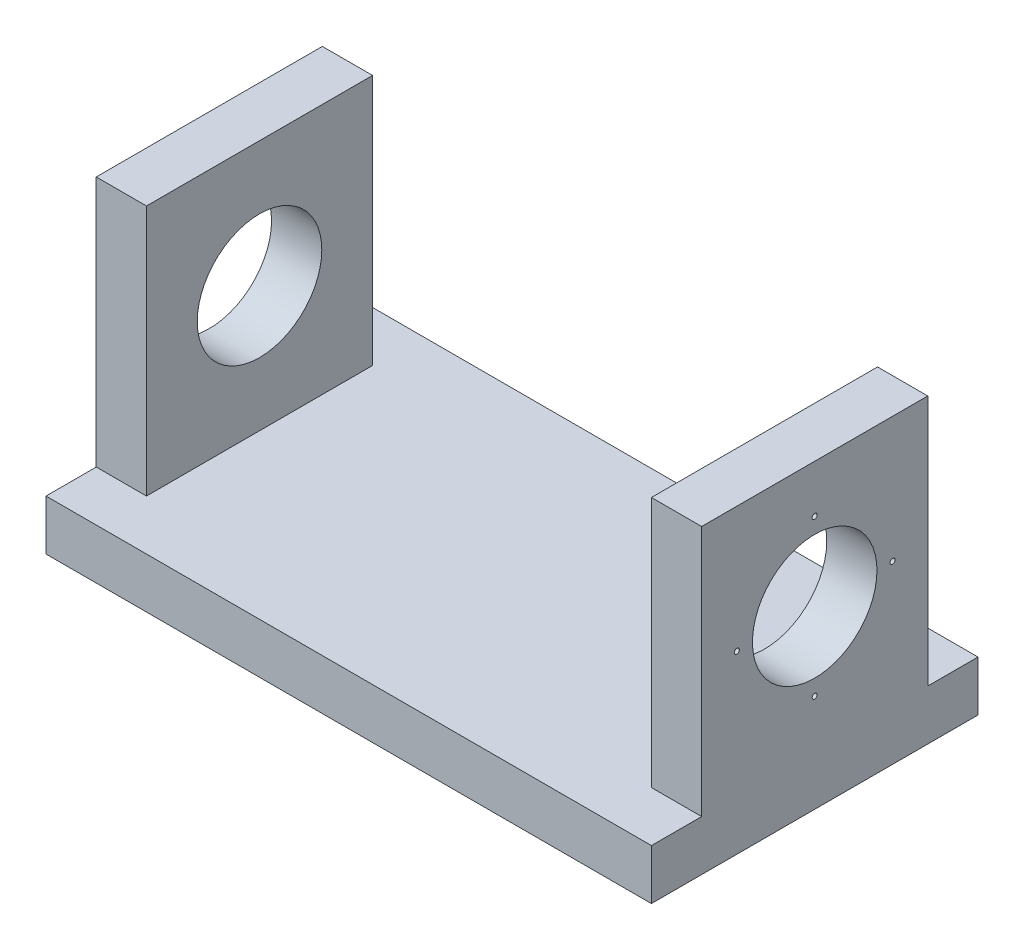
SolidWorks part; units mm, degrees
ref_plane "Front Plane" through (0, 0, 0) normal (0, 0, 1) x (1, 0, 0)
ref_plane "Top Plane" through (0, 0, 0) normal (0, 1, 0) x (1, 0, 0)
ref_plane "Right Plane" through (0, 0, 0) normal (1, 0, 0) x (0, 0, -1)
sketch "Sketch2" plane through (0, 0, 0) normal (0, 1, 0) x (1, 0, 0)
  line L0 (100.5, 45) -> (120.5, 45)
  line L1 (100.5, 45) -> (100.5, -45)
  line L2 (100.5, -45) -> (120.5, -45)
  line L3 (-100.2, -480) -> (100.2, -480) construction
  line L4 (100.2, -480) -> (100.2, 480) construction
  line L5 (100.2, 480) -> (-100.2, 480) construction
  line L6 (-100.2, 480) -> (-100.2, -480) construction
  line L7 (120.5, 45) -> (120.5, -45)
  line L8 (-100.5, 45) -> (-120.5, 45)
  line L9 (-100.5, 45) -> (-100.5, -45)
  line L10 (-100.5, -45) -> (-120.5, -45)
  line L11 (-120.5, 45) -> (-120.5, -45)
  line L12 (-120.5, -12.5) -> (120.5, -12.5) construction
  line L13 (-120.5, -12.5) -> (-120.5, 12.5) construction
  line L14 (-120.5, 12.5) -> (120.5, 12.5) construction
  line L15 (120.5, -12.5) -> (120.5, 12.5) construction
  line L16 (-120.5, -12.5) -> (120.5, 12.5) construction
  line L17 (-120.5, 12.5) -> (120.5, -12.5) construction
  circle A0 centre (0, 0) radius 128.6283
  circle A1 centre (0, 0) radius 55
  circle A2 centre (0, 0) radius 48.4
  point P13 (0, 0)
sketch "Sketch3" plane through (0, 0, 0) normal (0, 1, 0) x (1, 0, 0)
  line L0 (100.5, 45) -> (120.5, 45) construction
  line L1 (120.5, 45) -> (120.5, -45) construction
  line L2 (100.5, -45) -> (120.5, -45) construction
  line L3 (100.5, 45) -> (100.5, -45) construction
  line L4 (-100.5, 45) -> (-120.5, 45) construction
  line L5 (-120.5, 45) -> (-120.5, -45) construction
  line L6 (-100.5, -45) -> (-120.5, -45) construction
  line L7 (-100.5, 45) -> (-100.5, -45) construction
  line L8 (100.5, 45) -> (120.5, 45)
  line L9 (120.5, 45) -> (120.5, -45)
  line L10 (100.5, -45) -> (120.5, -45)
  line L11 (100.5, 45) -> (100.5, -45)
  line L12 (-100.5, 45) -> (-120.5, 45)
  line L13 (-120.5, 45) -> (-120.5, -45)
  line L14 (-100.5, -45) -> (-120.5, -45)
  line L15 (-100.5, 45) -> (-100.5, -45)
  circle A0 centre (0, 0) radius 55 construction
  circle A1 centre (0, 0) radius 128.6283 construction
  circle A2 centre (0, 0) radius 55
  circle A3 centre (0, 0) radius 128.6283
sketch "Sketch5" plane through (0, 0, 0) normal (0, 1, 0) x (1, 0, 0)
  line L0 (-120.5, 45) -> (-120.5, -45) construction
  line L1 (-120.5, -65) -> (120.5, -65)
  line L2 (-120.5, -65) -> (-120.5, 65)
  line L3 (-120.5, 65) -> (120.5, 65)
  line L4 (120.5, -65) -> (120.5, 65)
  line L5 (-120.5, -65) -> (120.5, 65) construction
  line L6 (-120.5, 65) -> (120.5, -65) construction
  point P0 (0, 0)
  dimension "D1" = 130
extrude "Boss-Extrude2" add sketch "Sketch5" against normal blind 20
sketch "Sketch6" plane through (0, 0, 0) normal (0, 1, 0) x (1, 0, 0)
  line L0 (100.5, 45) -> (120.5, 45) construction
  line L1 (120.5, 45) -> (120.5, -45) construction
  line L2 (100.5, -45) -> (120.5, -45) construction
  line L3 (100.5, 45) -> (100.5, -45) construction
  line L4 (-100.5, 45) -> (-120.5, 45) construction
  line L5 (-120.5, 45) -> (-120.5, -45) construction
  line L6 (-100.5, -45) -> (-120.5, -45) construction
  line L7 (-100.5, 45) -> (-100.5, -45) construction
  line L8 (100.5, 45) -> (120.5, 45)
  line L9 (120.5, 45) -> (120.5, -45)
  line L10 (100.5, -45) -> (120.5, -45)
  line L11 (100.5, 45) -> (100.5, -45)
  line L12 (-100.5, 45) -> (-120.5, 45)
  line L13 (-120.5, 45) -> (-120.5, -45)
  line L14 (-100.5, -45) -> (-120.5, -45)
  line L15 (-100.5, 45) -> (-100.5, -45)
extrude "Boss-Extrude3" add sketch "Sketch6" along normal blind 100
sketch "Sketch7" plane through (-100.5, 0, 0) normal (1, 0, 0) x (0, 0, -1)
  line L0 (-60, 120) -> (60, 120)
  line L1 (-60, 120) -> (-60, 0)
  line L2 (-60, 0) -> (60, 0)
  line L3 (60, 120) -> (60, 0)
  line L4 (-45, 0) -> (45, 0)
  line L5 (45, 0) -> (45, 100)
  line L6 (45, 100) -> (-45, 100)
  line L7 (-45, 100) -> (-45, 0)
  line L8 (-45, 0) -> (45, 0)
  line L9 (45, 0) -> (45, 100)
  line L10 (45, 100) -> (-45, 100)
  line L11 (-45, 100) -> (-45, 0)
  line L12 (-45, 50) -> (45, 50) construction
  line L14 (-13, 63) -> (13, 63)
  line L15 (-13, 63) -> (-13, 37)
  line L16 (-13, 37) -> (13, 37)
  line L17 (13, 63) -> (13, 37)
  line L18 (0, 63) -> (0, 37) construction
  line L19 (13, 50) -> (-13, 50) construction
  circle A0 centre (0, 50) radius 18.3848 construction
  circle A1 centre (0, 50) radius 21.3848
  circle A2 centre (0, 50) radius 21.5848
  circle A3 centre (0, 50) radius 24.5848
  dimension "D1" = 0
sketch "Sketch8" plane through (120.5, 0, 0) normal (1, 0, 0) x (0, 0, -1)
  circle A2 centre (0, 50) radius 24.5848 construction
  circle A3 centre (0, 50) radius 24.5848 construction
  circle A4 centre (0, 50) radius 24.7848
  dimension "D1" = 0.2
extrude "Cut-Extrude1" cut sketch "Sketch8" against normal through all both and the other way through all
sketch "Sketch9" plane through (0, -20, 0) normal (0, -1, 0) x (1, 0, 0)
  circle A0 centre (0, 0) radius 15.5
  dimension "D1" = 31
extrude "Cut-Extrude2" cut sketch "Sketch9" against normal blind 10
sketch "Sketch10" plane through (120.5, 0, 0) normal (1, 0, 0) x (0, 0, -1)
  circle A0 centre (0, 81) radius 1
  circle A1 centre (-31, 50) radius 1
  circle A2 centre (31, 50) radius 1
  circle A3 centre (0, 19) radius 1
extrude "Cut-Extrude3" cut sketch "Sketch10" against normal up to surface (20 mm away) up to face at (100.5, 50, -24.7848)
